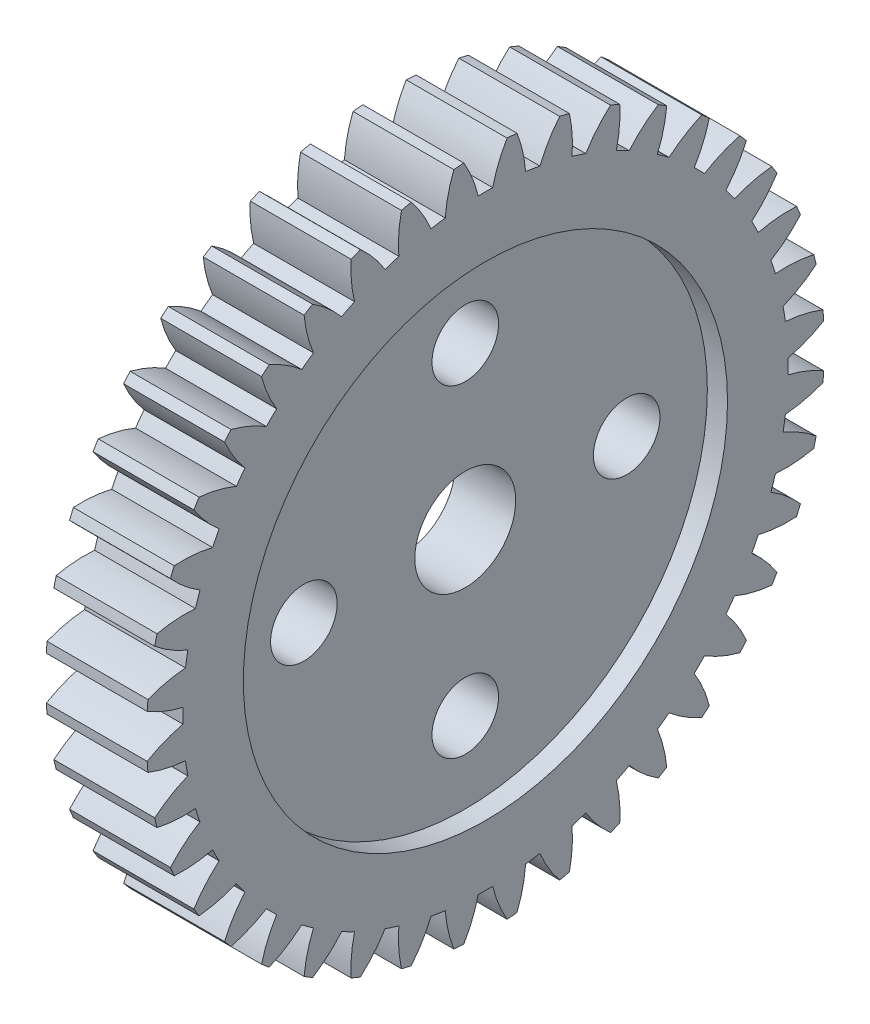
SolidWorks part; units mm, degrees
ref_plane "Plane1" through (0, 0, 0) normal (0, 0, 1) x (1, 0, 0)
ref_plane "Plane2" through (0, 0, 0) normal (0, 1, 0) x (1, 0, 0)
ref_plane "Plane3" through (0, 0, 0) normal (1, 0, 0) x (0, 0, -1)
other "Configuration Table"
sketch "HoldingSke" plane through (0, 0, 0) normal (0, 1, 0) x (1, 0, 0)
  line L0 (0, 0) -> (0.9576, -0.8035)
  line L1 (-15, 0) -> (100, 0) construction
  line L2 (0, 0) -> (-2.1039, 2.3779)
  line L3 (0, 0) -> (-11.863, 4.5341)
  line L4 (0, 0) -> (6.6156, 5.5511)
  line L5 (0, 0) -> (-46.8476, -17.4728)
  line L6 (0, 0) -> (-4.1448, -2.7965)
  line L7 (-2.1039, 2.3779) -> (8.6586, 51.2059)
  line L8 (-76.2, 54.61) -> (-75.3, 54.61)
  line L9 (-71.009, 38.7566) -> (-53.1078, 45.2721)
  line L10 (-76.2, 71.12) -> (104.1128, 71.12)
  line L11 (0, 0) -> (-5, 0)
  line L12 (-76.2, 101.6) -> (-76.17, 101.6)
  line L13 (24.9733, 27.94) -> (52.9518, 28.4284)
  line L14 (24.9733, 27.94) -> (24.9743, 27.94)
  line L15 (24.9733, 27.94) -> (100.4006, 29.5858)
  line L16 (-63.627, -0.8) -> (-12.827, -0.8)
  circle A0 centre (0, 0) radius 2.5
  circle A1 centre (0, 0) radius 14.999
  circle A2 centre (0, 0) radius 37.5
  circle A3 centre (0, 0) radius 2.5
  dimension "MHD" = 29.998
  dimension "Hub_dia" = 75
  dimension "Bore" = 5
  dimension "MBD" = 5
  dimension "Num_teeth" = 40
  dimension "Pitch" = 1.25
  dimension "Overall_len" = 50
  dimension "Show_teeth" = 40
  dimension "Thickness" = 5
  dimension "OAL" = 50.0001
  dimension "T_dim" = 0.9
  dimension "Ap" = 20
  dimension "H" = 19.05
  dimension "Pitch_radius" = 180.3128
  dimension "Width" = 5
  dimension "Backlash" = 0.03
  dimension "Addendum_fac" = 1
  dimension "Dedendum_fac" = 1.25
  dimension "Clearance_fac" = 0.25
  dimension "Dedendum_add" = 0.001
  dimension "Module" = 0.8
sketch "BasProSke" plane through (0, 0, 0) normal (0, 1, 0) x (1, 0, 0)
  line L0 (-10, 0) -> (60, 0) construction
  line L1 (0, 0) -> (0, 16.8)
  line L2 (0, 0) -> (5, 0)
  line L3 (5, 0) -> (5, 16.8)
  line L4 (5, 16.8) -> (0, 16.8)
  dimension "Thickness" = 5
  dimension "Diameter" = 33.6
revolve "Base-Revolve" add sketch "BasProSke" angle 360 about L0
sketch "TooCutSke" plane through (0, 0, 0) normal (1, 0, 0) x (0, 0, -1)
  line L1 (0, 0) -> (0, 107) construction
  line L2 (0, 0) -> (-0.6807, 15.9855) construction
  line L3 (0, 0) -> (-2.5091, 31.8807) construction
  line L4 (-0.6807, 15.9855) -> (-1.2545, 15.9404) construction
  arc A0 (0.3582, 14.9947) -> (-0.3582, 14.9947) centre (0, 0) ccw
  arc A1 (1.086, 16.7903) -> (-1.086, 16.7903) centre (0, 0) ccw
  circle A2 centre (0, 0) radius 16 construction
  circle A3 centre (0, 0) radius 15.0351 construction
  arc A4 (-0.3582, 14.9947) -> (-1.086, 16.7903) centre (-6.5851, 13.5163) ccw
  arc A5 (1.086, 16.7903) -> (0.3582, 14.9947) centre (6.5851, 13.5163) ccw
  dimension "Root_dia" = 29.998
  dimension "Overcut_dia" = 33.6508
  dimension "Pitch_dia" = 32
  dimension "Base_dia" = 30.0702
  dimension "Flank_rad" = 6.4
  dimension "Half_ang" = 4.5
  dimension "Half_CT" = 0.5757
extrude "ToothCut" cut sketch "TooCutSke" along normal through all
fillet "Breaks" [suppressed] radius 0.016
fillet "RootFillets" [suppressed] radius 0.201
pattern_circular "TeethCuts" count 40 every 9 about axis through (-10, 0, 0) along (1, 0, 0) of "ToothCut", "RootFillets", "Breaks"
sketch "HubNeaOneSke" plane through (0, 0, 0) normal (-1, 0, 0) x (0, 0, 1)
  circle A0 centre (0, 0) radius 14.999
  dimension "Diameter" = 29.998
extrude "HubNearOne" [suppressed] add sketch "HubNeaOneSke" along normal blind 45.0001
sketch "HubNeaBotSke" plane through (0, 0, 0) normal (-1, 0, 0) x (0, 0, 1)
  circle A0 centre (0, 0) radius 14.999
  dimension "Diameter" = 29.998
extrude "HubNearBoth" [suppressed] add sketch "HubNeaBotSke" along normal blind 22.5
ref_plane "FarPln" through (5, 0, 0) normal (1, 0, 0) x (0, 0, -1)
sketch "HubFarSke" plane through (5, 0, 0) normal (1, 0, 0) x (0, 0, -1)
  circle A0 centre (0, 0) radius 14.999
  dimension "Diameter" = 29.998
extrude "HubFar" [suppressed] add sketch "HubFarSke" along normal blind 22.5
sketch "BorSke" plane through (0, 0, 0) normal (1, 0, 0) x (0, 0, -1)
  circle A0 centre (0, 0) radius 2.5
  dimension "Diameter" = 5
extrude "Bore" cut sketch "BorSke" along normal mid plane 100.0001
sketch "KeySke" plane through (0, 0, 0) normal (1, 0, 0) x (0, 0, -1)
  line L0 (-1, 0) -> (-1, 3.4)
  line L1 (-1, 3.4) -> (1, 3.4)
  line L2 (1, 3.4) -> (1, 0)
  line L3 (0, 0) -> (0, 34) construction
  line L4 (-1, 0) -> (1, 0)
  dimension "Offset" = 3.4
  dimension "Width" = 2
extrude "Keyway" [suppressed] cut sketch "KeySke" along normal mid plane 100.0001
pattern_circular "Keyway2" [suppressed] count 2 every 90 about axis through (-10, 0, 0) along (1, 0, 0)
sketch "草图1" plane through (5, 0, 0) normal (1, 0, 0) x (0, 0, -1)
  circle A0 centre (0, 0) radius 8 construction
  circle A1 centre (8, 0) radius 1.65
  circle A2 centre (0, -8) radius 1.65
  circle A3 centre (0, 0) radius 8 construction
  circle A4 centre (-8, 0) radius 1.65
  circle A5 centre (0, 0) radius 8 construction
  circle A6 centre (0, 8) radius 1.65
  circle A7 centre (0, 0) radius 8 construction
  point P17 (0, 0)
  dimension "D1" = 16
  dimension "D2" = 3.3
  dimension "D3" = 4
extrude "切除-拉伸1" cut sketch "草图1" against normal blind 10
sketch "草图2" plane through (0, 0, 0) normal (-1, 0, 0) x (0, 0, 1)
  circle A0 centre (0, 0) radius 12
  dimension "D1" = 24
extrude "切除-拉伸2" cut sketch "草图2" against normal blind 1
sketch "草图3" plane through (5, 0, 0) normal (1, 0, 0) x (0, 0, -1)
  circle A0 centre (0, 0) radius 12
  dimension "D1" = 24
extrude "切除-拉伸3" cut sketch "草图3" against normal blind 1
equation "' \"Module@HoldingSke\" = 6.35"
equation "' \"Num_teeth@HoldingSke\" = 12"
equation "' \"Ap@HoldingSke\" =  20"
equation "' \"Ap@HoldingSke\" = 20"
equation "' \"Width@HoldingSke\" = 0.5 * 25.4"
equation "' \"Hub_dia@HoldingSke\"= 1 * 25.4"
equation "' \"Hub_dia@HoldingSke\" = 1 * 25.4"
equation "' \"Overall_len@HoldingSke\" = 1.0 * 25.4"
equation "' \"Bore@HoldingSke\" = 0.75 * 25.4"
equation "' \"T_dim@HoldingSke\" = 0.1 * 25.4"
equation "' \"Width@KeySke\" = 0.25 * 25.4"
equation "' \"Show_teeth@HoldingSke\" = 13"
equation "' \"Backlash@HoldingSke\" = 0.009 * 25.4"
equation "' \"Addendum_fac@HoldingSke\" = 1.0"
equation "' \"Dedendum_fac@HoldingSke\" = 1.25"
equation "' \"Dedendum_add@HoldingSke\" = 0.00005 * 25.4"
equation "' \"Clearance_fac@HoldingSke\" = 0.25"
equation "\"Pitch@HoldingSke\" = 1 / \"Module@HoldingSke\""
equation "\"Overcut_dia@TooCutSke\" = (\"Num_teeth@HoldingSke\" + 2 * \"Addendum_fac@HoldingSke\") / \"Pitch@HoldingSke\" + 0.002 * 25.4"
equation "\"Pitch_dia@TooCutSke\" = \"Num_teeth@HoldingSke\" / \"Pitch@HoldingSke\""
equation "\"Base_dia@TooCutSke\" = \"Num_teeth@HoldingSke\" / \"Pitch@HoldingSke\" * cos((\"Ap@HoldingSke\"  * 3.14159265 / 180))"
equation "\"Root_dia@TooCutSke\" = (\"Num_teeth@HoldingSke\" + 2) / \"Pitch@HoldingSke\" - 2 * (\"Addendum_fac@HoldingSke\" + \"Dedendum_fac@HoldingSke\") / \"Pitch@HoldingSke\" - \"Dedendum_add@HoldingSke\" * 2"
equation "\"Half_ang@TooCutSke\" = 180 / \"Num_teeth@HoldingSke\""
equation "\"Half_CT@TooCutSke\" = \"Num_teeth@HoldingSke\" / \"Pitch@HoldingSke\" * sin((3.14159265 / 2 / \"Num_teeth@HoldingSke\")) / 2 - 7 * \"Backlash@HoldingSke\" / 4"
equation "\"Flank_rad@TooCutSke\" = \"Num_teeth@HoldingSke\" / \"Pitch@HoldingSke\" / 5"
equation "\"Radius@RootFillets\" = \"Clearance_fac@HoldingSke\" / \"Pitch@HoldingSke\" + \"Dedendum_add@HoldingSke\""
equation "\"Break_rad@Breaks\" = 0.02 / \"Pitch@HoldingSke\""
equation "\"Thickness@HoldingSke\" = \"Width@HoldingSke\""
equation "\"OAL@HoldingSke\" = \"Thickness@HoldingSke\""
equation "\"MHD@HoldingSke\" = (\"Num_teeth@HoldingSke\" + 2) / \"Pitch@HoldingSke\" - 2 * (\"Addendum_fac@HoldingSke\" + \"Dedendum_fac@HoldingSke\")  / \"Pitch@HoldingSke\" - \"Dedendum_add@HoldingSke\" * 2"
equation "\"MBD@HoldingSke\" = (\"Num_teeth@HoldingSke\" + 2) / \"Pitch@HoldingSke\" - 2 * (\"Addendum_fac@HoldingSke\" + \"Dedendum_fac@HoldingSke\")  / \"Pitch@HoldingSke\" - \"Dedendum_add@HoldingSke\" * 2 - 0.002 * 25.4"
equation "\"MHD@HoldingSke\" = ((sgn( \"MHD@HoldingSke\" - \"Hub_dia@HoldingSke\" )-1)*( \"MHD@HoldingSke\" - \"Hub_dia@HoldingSke\" ))/-2+ \"Hub_dia@HoldingSke\""
equation "\"MBD@HoldingSke\" = ((sgn( \"MBD@HoldingSke\" - \"Bore@HoldingSke\" )-1)*( \"MBD@HoldingSke\" - \"Bore@HoldingSke\" ))/-2+ \"Bore@HoldingSke\""
equation "\"OAL@HoldingSke\" = ((sgn( \"OAL@HoldingSke\" - \"Overall_len@HoldingSke\" )+1)*( \"OAL@HoldingSke\" - \"Overall_len@HoldingSke\" ))/2 + \"Overall_len@HoldingSke\" + 0.000002 * 25.4"
equation "\"Num_teeth@TeethCuts\" = int( \"Show_teeth@HoldingSke\" ) + 1"
equation "\"Num_teeth@TeethCuts\" = ((sgn( \"Num_teeth@TeethCuts\" - \"Num_teeth@HoldingSke\" )-1)*( \"Num_teeth@TeethCuts\" - \"Num_teeth@HoldingSke\" ))/-2+ \"Num_teeth@HoldingSke\""
equation "\"Num_teeth@TeethCuts\" = ((sgn( \"Num_teeth@TeethCuts\" - 2.0)+1)*( \"Num_teeth@TeethCuts\" - 2.0))/2 +2.0"
equation "\"Angle@TeethCuts\" = 360.0 / \"Num_teeth@HoldingSke\""
equation "\"Diameter@BasProSke\" = (\"Num_teeth@HoldingSke\" + 2 * \"Addendum_fac@HoldingSke\") / \"Pitch@HoldingSke\""
equation "\"Thickness@BasProSke\"  = \"Thickness@HoldingSke\""
equation "' \"Fillet_rad@BasProSke\" =  \"Thickness@HoldingSke\" * 0.05"
equation "' \"Fillet_rad@BasProSke\" = \"Thickness@HoldingSke\" * 0.05"
equation "\"MHD@HoldingSke\" = ((sgn( \"MHD@HoldingSke\" - \"Root_dia@TooCutSke\" )-1)*( \"MHD@HoldingSke\" - \"Root_dia@TooCutSke\" ))/-2+ \"Root_dia@TooCutSke\""
equation "\"Diameter@HubNeaOneSke\" = \"MHD@HoldingSke\""
equation "\"Length@HubNearOne\" = \"OAL@HoldingSke\" - \"Thickness@BasProSke\""
equation "\"Diameter@HubNeaBotSke\" = \"MHD@HoldingSke\""
equation "\"Length@HubNearBoth\" = ( \"OAL@HoldingSke\" - \"Thickness@BasProSke\" ) / 2.0"
equation "\"Thickness@FarPln\" = \"Thickness@BasProSke\""
equation "\"Diameter@HubFarSke\" = \"MHD@HoldingSke\""
equation "\"Length@HubFar\" = ( \"OAL@HoldingSke\" - \"Thickness@BasProSke\" ) / 2.0"
equation "\"Diameter@BorSke\" = \"MBD@HoldingSke\""
equation "\"D1@Bore\" = \"OAL@HoldingSke\" * 2.0"
equation "\"D1@Keyway\" = \"OAL@HoldingSke\" * 2.0"
equation "\"Offset@KeySke\" = \"T_dim@HoldingSke\" + \"MBD@HoldingSke\" / 2.0"
